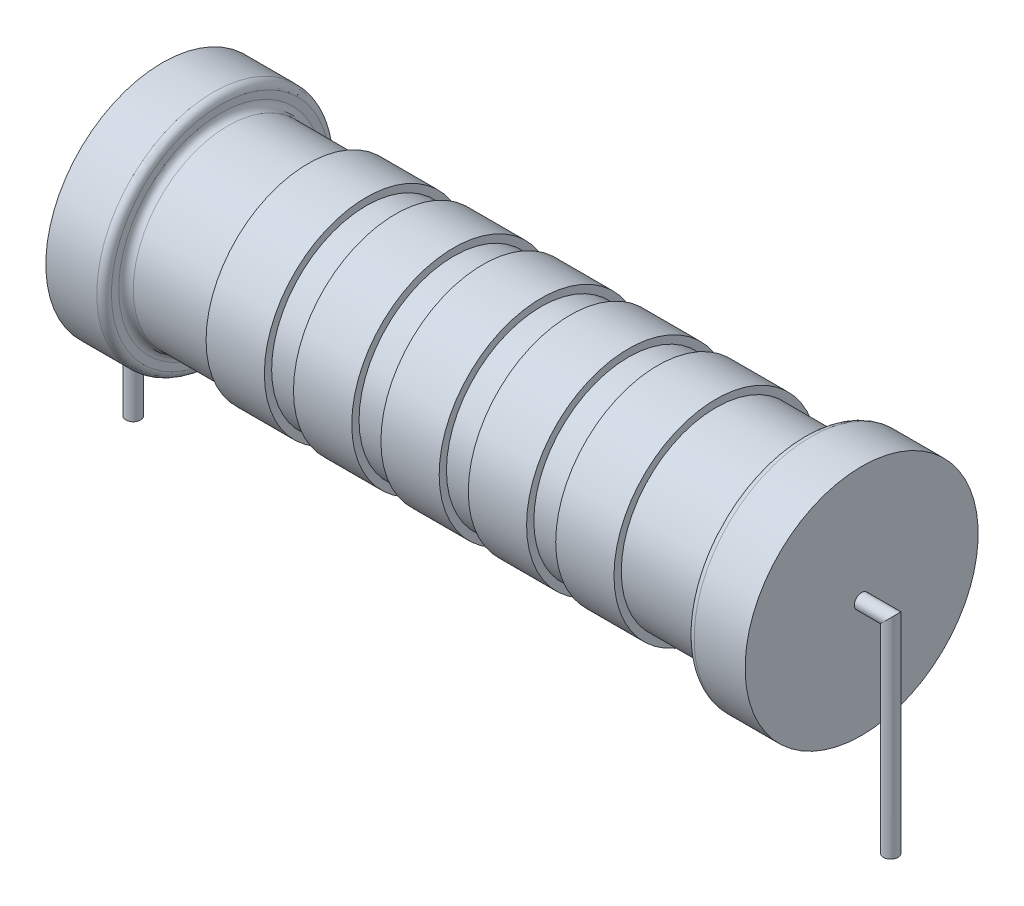
SolidWorks part; units mm, degrees
ref_plane "前视基准面" through (0, 0, 0) normal (0, 0, 1) x (1, 0, 0)
ref_plane "上视基准面" through (0, 0, 0) normal (0, 1, 0) x (1, 0, 0)
ref_plane "右视基准面" through (0, 0, 0) normal (1, 0, 0) x (0, 0, -1)
sketch "草图1" plane through (0, 0, 0) normal (0, 0, 1) x (1, 0, 0)
  line L0 (-328.0744, 0) -> (16075.6443, 0) construction
  line L1 (0, -328.0744) -> (0, 16075.6443) construction
  line L2 (-12, 0) -> (-12, 4)
  line L3 (-12, 4) -> (-10, 4)
  line L4 (-10, 4) -> (-10, 3.25)
  line L5 (-10, 3.25) -> (10, 3.25)
  line L11 (12, 0) -> (12, 4)
  line L12 (10, 4) -> (10, 3.25)
  line L13 (12, 4) -> (10, 4)
  line L14 (-12, 0) -> (12, 0)
  point P1 (-12, 0)
  point P5 (12, 0)
  point P10 (-12, 0)
  point P17 (0, -3.25)
  point P22 (0, 3.25)
  dimension "D1" = 24
  dimension "D3" = 2
  dimension "D4" = 0.75
revolve "旋转2" add sketch "草图1" angle 360 about L14
fillet "圆角1" radius 0.25 4 edges at (10, -3.25, 0) (10, -4, 0) (-10, -3.25, 0) (-10, -4, 0)
sketch "草图2" plane through (0, 0, 0) normal (0, 0, 1) x (1, 0, 0)
  line L0 (0, -1000) -> (0, 49000) construction
  line L1 (9.75, 3.25) -> (-9.75, 3.25) construction
  line L6 (-1000, 0) -> (49000, 0) construction
  line L7 (2, 3.5) -> (4, 3.5)
  line L8 (-1, 3) -> (1, 3)
  line L9 (-1, 3) -> (-1, 3.5)
  line L10 (-1, 3.5) -> (1, 3.5)
  line L11 (1, 3) -> (1, 3.5)
  line L12 (-1, 3) -> (1, 3.5) construction
  line L13 (-1, 3.5) -> (1, 3) construction
  line L14 (4, 3) -> (4, 3.5)
  line L15 (2, 3) -> (4, 3)
  line L16 (2, 3) -> (2, 3.5)
  line L17 (5, 3.5) -> (7, 3.5)
  line L18 (7, 3) -> (7, 3.5)
  line L19 (5, 3) -> (7, 3)
  line L20 (5, 3) -> (5, 3.5)
  line L21 (-4, 3.5) -> (-2, 3.5)
  line L22 (-2, 3) -> (-2, 3.5)
  line L23 (-4, 3) -> (-2, 3)
  line L24 (-4, 3) -> (-4, 3.5)
  line L25 (-7, 3.5) -> (-5, 3.5)
  line L26 (-5, 3) -> (-5, 3.5)
  line L27 (-7, 3) -> (-5, 3)
  line L28 (-7, 3) -> (-7, 3.5)
  point P1 (0, 3.25)
  point P9 (0, 3.25)
  dimension "D1" = 2
  dimension "D2" = 0.5
  dimension "D3" = 3
  dimension "D4" = 3
revolve "旋转3" add sketch "草图2" angle 360 about L6
sketch "草图3" plane through (0, 0, 0) normal (0, 0, 1) x (1, 0, 0)
  line L0 (-12, 4) -> (-12, -4) construction
  line L1 (-12, 0) -> (-13, 0)
  line L2 (-13, 0) -> (-13, -7)
  line L3 (0, -1000) -> (0, 49000) construction
  point P0 (-12, 0)
  dimension "D1" = 1
  dimension "D2" = 7
sweep "扫描1" add path "草图3" circular profile diameter 0.5 parameters "D3"=0.5
mirror "镜向1" about plane through (0, 0, 0) normal (1, 0, 0) of "扫描1"
sketch "草图23" plane through (0, 0, 0) normal (0, 1, 0) x (1, 0, 0)
  line L0 (-12, 4) -> (-12, -4) construction
  point P0 (13, 0)
  point P1 (-13, 0)
  dimension "D1" = 26
